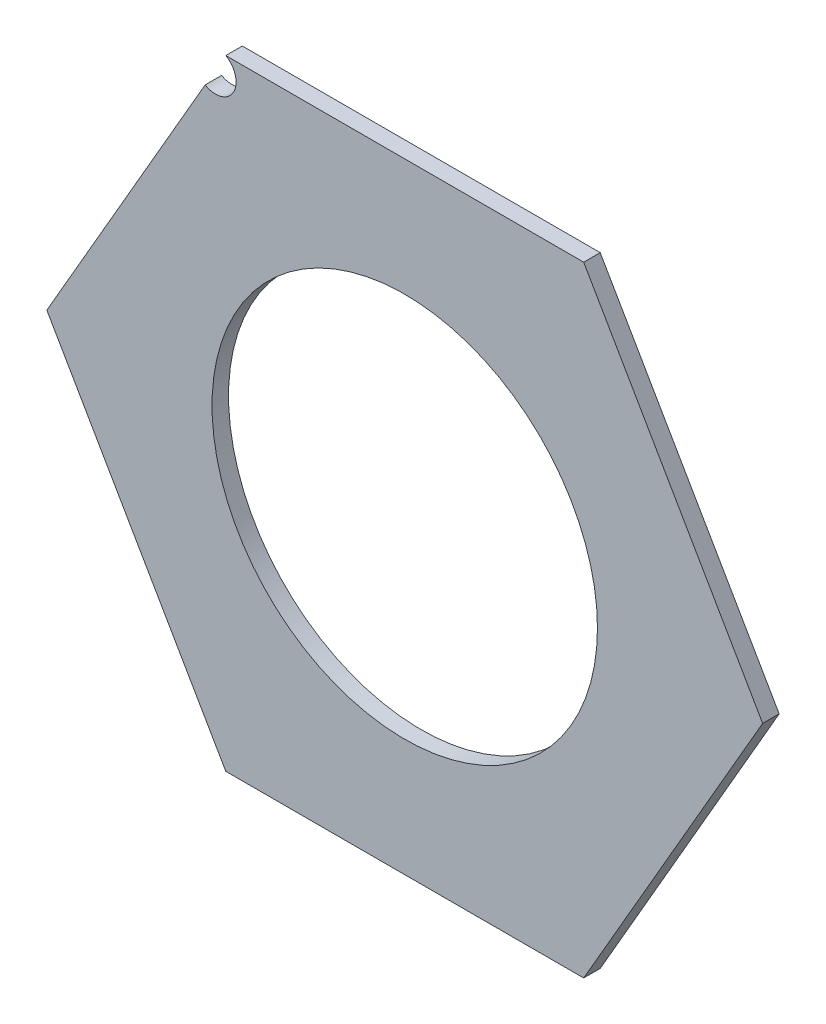
SolidWorks part; units mm, degrees
ref_plane "Alzado" through (0, 0, 0) normal (0, 0, 1) x (1, 0, 0)
ref_plane "Planta" through (0, 0, 0) normal (0, 1, 0) x (1, 0, 0)
ref_plane "Vista lateral" through (0, 0, 0) normal (1, 0, 0) x (0, 0, -1)
sketch "Croquis2" plane through (0, 0, 0) normal (0, 0, 1) x (1, 0, 0)
  line L7 (-65, 0) -> (-32.5, -56.2917)
  line L8 (-32.5, -56.2917) -> (32.5, -56.2917)
  line L9 (32.5, -56.2917) -> (65, 0)
  line L10 (65, 0) -> (32.5, 56.2917)
  line L11 (32.5, 56.2917) -> (-32.5, 56.2917)
  line L12 (-36.25, 49.7965) -> (-65, 0)
  circle A3 centre (0, 0) radius 56.2917 construction
  circle A4 centre (0, 0) radius 35
  arc A6 (-36.25, 49.7965) -> (-32.5, 56.2917) centre (-34.375, 53.0441) ccw
  dimension "D2" = 70
  dimension "D3" = 7.5
  dimension "D1" = 65
extrude "Saliente-Extruir1" add sketch "Croquis2" along normal blind 3
